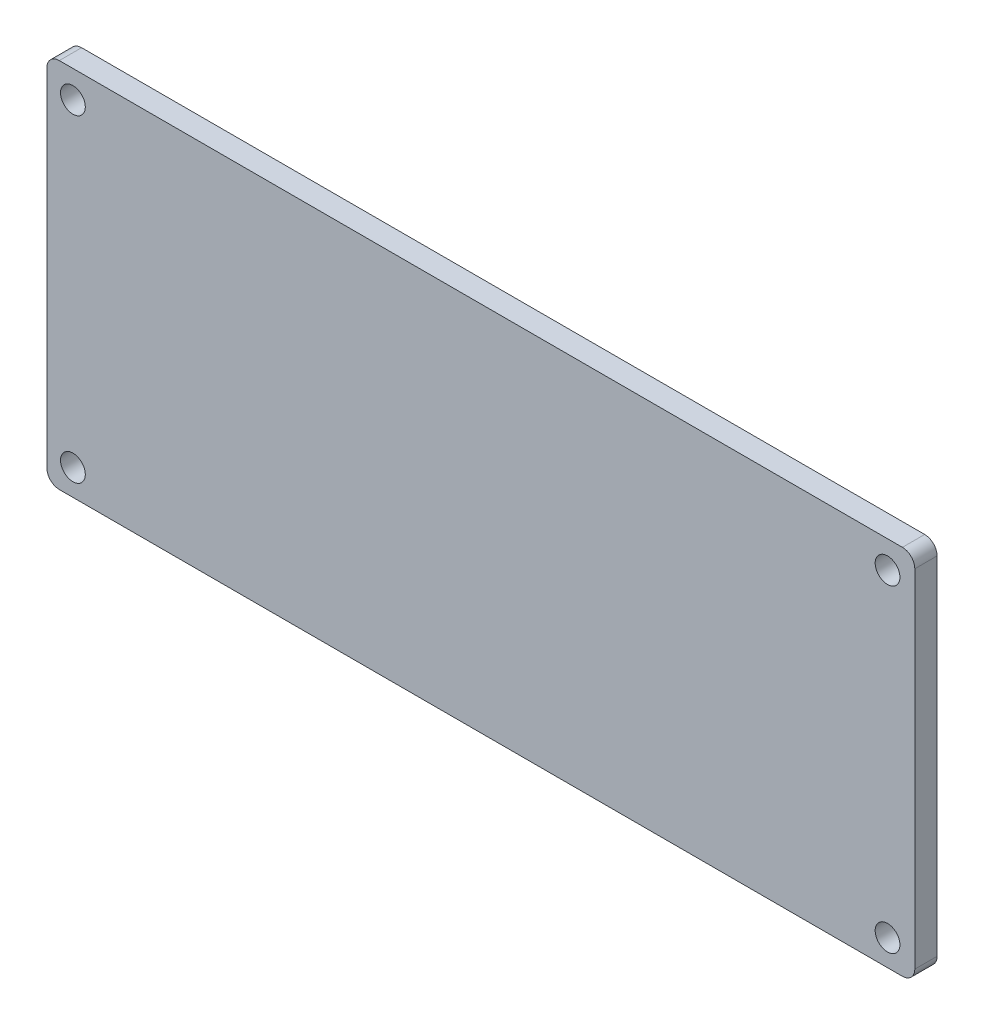
SolidWorks part; units mm, degrees
ref_plane "前基準面" through (0, 0, 0) normal (0, 0, 1) x (1, 0, 0)
ref_plane "上基準面" through (0, 0, 0) normal (0, 1, 0) x (1, 0, 0)
ref_plane "右基準面" through (0, 0, 0) normal (1, 0, 0) x (0, 0, -1)
sketch "草圖1" plane through (0, 0, 0) normal (0, 0, 1) x (1, 0, 0)
  line L1 (-34.4277, 23.0561) -> (35.6523, 23.0561)
  line L2 (-34.4277, 23.0561) -> (-34.4277, -6.9439)
  line L3 (-34.4277, -6.9439) -> (35.6523, -6.9439)
  line L4 (35.6523, 23.0561) -> (35.6523, -6.9439)
  dimension "D1" = 70.08
  dimension "D2" = 30
extrude "填料-伸長1" add sketch "草圖1" along normal blind 1.8
fillet "圓角1" radius 1 4 edges at (-34.4277, 23.0561, 0.9) (-34.4277, -6.9439, 0.9) (35.6523, -6.9439, 0.9) (35.6523, 23.0561, 0.9)
sketch "草圖2" plane through (0, 0, 1.8) normal (0, 0, 1) x (1, 0, 0)
  line L0 (34.6523, 23.0561) -> (-33.4277, 23.0561) construction
  line L1 (-34.4277, 22.0561) -> (-34.4277, -5.9439) construction
  line L3 (35.6523, -5.9439) -> (35.6523, 22.0561) construction
  line L5 (-33.4277, -6.9439) -> (34.6523, -6.9439) construction
  circle A0 centre (-32.3277, 20.8561) radius 1
  circle A1 centre (-32.3277, -4.8439) radius 1
  circle A2 centre (33.4523, -4.8439) radius 1
  circle A3 centre (33.4523, 20.8561) radius 1
  dimension "D1" = 2
  dimension "D2" = 2
  dimension "D3" = 2
  dimension "D4" = 2
  dimension "D5" = 2.2
  dimension "D6" = 2.1
  dimension "D7" = 2.1
  dimension "D9" = 2.2
  dimension "D10" = 2.2
  dimension "D11" = 2.1
  dimension "D12" = 2.1
  dimension "D8" = 2.2
extrude "除料-伸長1" cut sketch "草圖2" against normal blind 1.8
